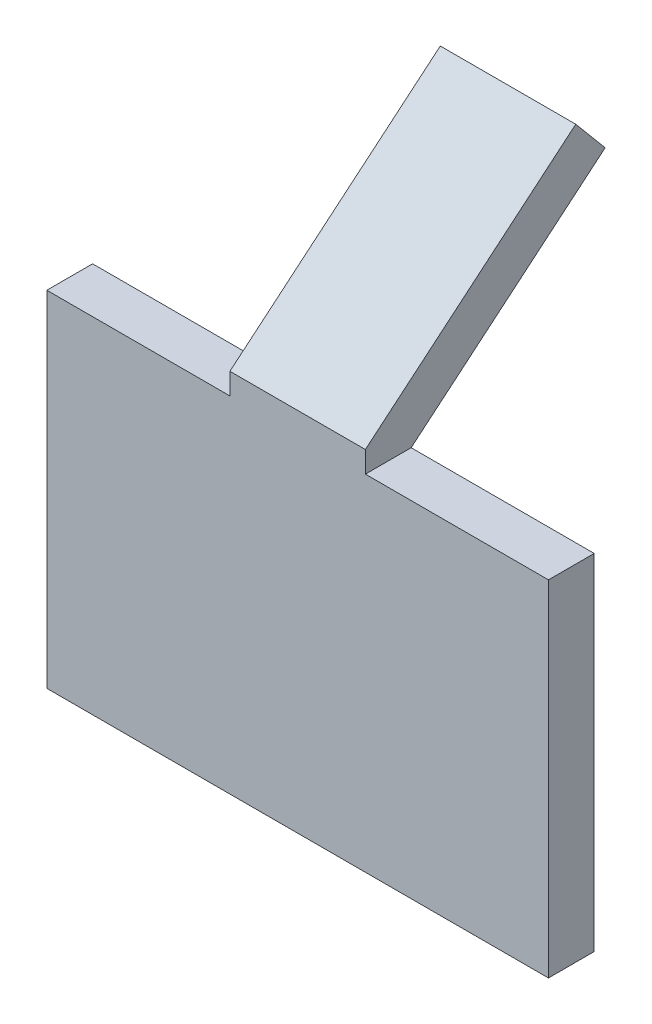
SolidWorks part; units mm, degrees
ref_plane "Front Plane" through (0, 0, 0) normal (0, 0, 1) x (1, 0, 0)
ref_plane "Top Plane" through (0, 0, 0) normal (0, 1, 0) x (1, 0, 0)
ref_plane "Right Plane" through (0, 0, 0) normal (1, 0, 0) x (0, 0, -1)
sketch "Sketch1" plane through (0, 0, 0) normal (1, 0, 0) x (0, 0, -1)
  line L0 (0, 0) -> (0, -50.8)
  line L1 (0, -50.8) -> (6.35, -50.8)
  line L2 (6.35, -50.8) -> (6.35, -2.9611)
  line L3 (6.35, -2.9611) -> (33.268, 19.6258)
  line L4 (33.268, 19.6258) -> (29.1863, 24.4902)
  line L5 (29.1863, 24.4902) -> (0, 0)
  dimension "D1" = 130
  dimension "D2" = 130
  dimension "D3" = 6.35
  dimension "D4" = 6.35
  dimension "D5" = 50.8
  dimension "D6" = 38.1
extrude "Boss-Extrude1" add sketch "Sketch1" along normal blind 18.796
sketch "Sketch2" plane through (18.796, 0, 0) normal (1, 0, 0) x (0, 0, -1)
  line L1 (6.35, -2.9611) -> (0, -2.9611)
  line L2 (6.35, -2.9611) -> (6.35, -50.8)
  line L3 (6.35, -50.8) -> (0, -50.8)
  line L4 (0, -2.9611) -> (0, -50.8)
extrude "Boss-Extrude2" add sketch "Sketch2" along normal blind 25.4
sketch "Sketch3" plane through (0, 0, 0) normal (-1, 0, 0) x (0, 0, 1)
  line L1 (-6.35, -2.9611) -> (0, -2.9611)
  line L2 (-6.35, -2.9611) -> (-6.35, -50.8)
  line L3 (-6.35, -50.8) -> (0, -50.8)
  line L4 (0, -2.9611) -> (0, -50.8)
extrude "Boss-Extrude3" add sketch "Sketch3" along normal blind 25.4
